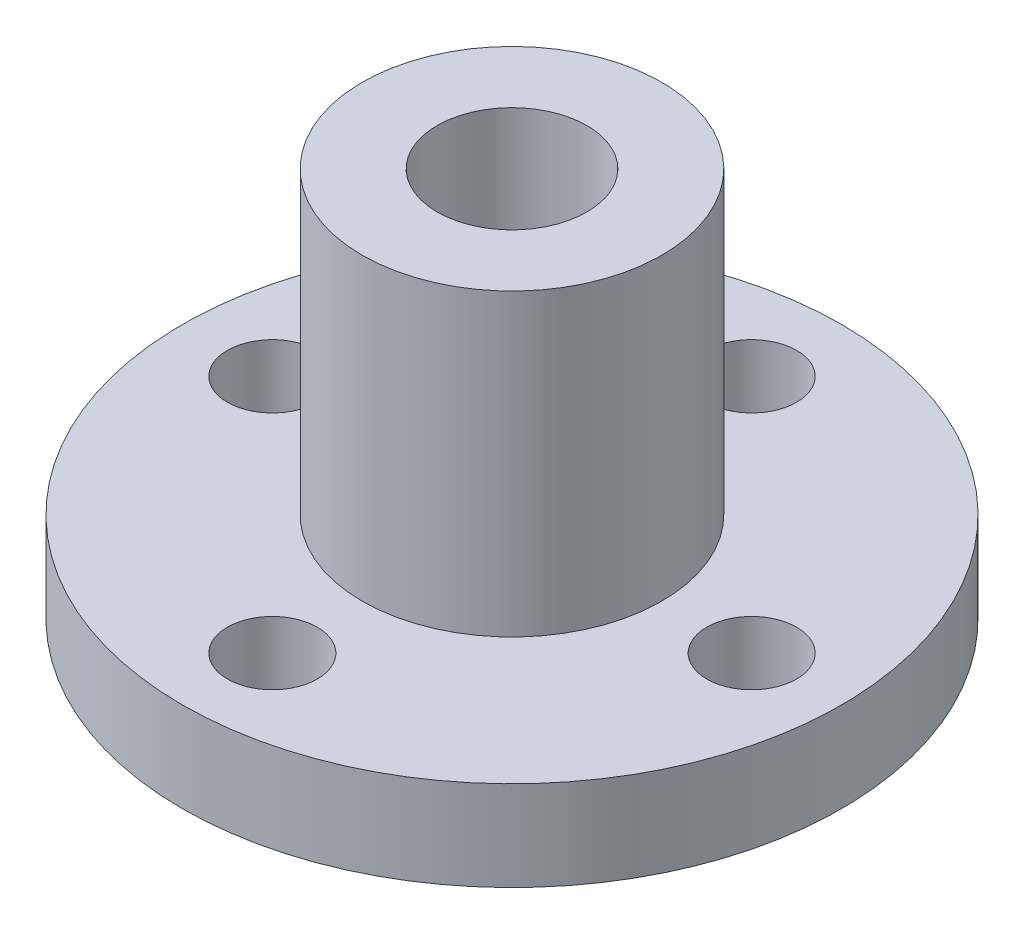
SolidWorks part; units mm, degrees
ref_plane "前视基准面" through (0, 0, 0) normal (0, 0, 1) x (1, 0, 0)
ref_plane "上视基准面" through (0, 0, 0) normal (0, 1, 0) x (1, 0, 0)
ref_plane "右视基准面" through (0, 0, 0) normal (1, 0, 0) x (0, 0, -1)
sketch "草图1" plane through (0, 0, 0) normal (0, 1, 0) x (1, 0, 0)
  circle A0 centre (0, 0) radius 11
  dimension "D1" = 22
extrude "凸台-拉伸1" add sketch "草图1" along normal blind 3
sketch "草图2" plane through (0, 3, 0) normal (0, 1, 0) x (1, 0, 0)
  circle A0 centre (0, 0) radius 5
  dimension "D1" = 10
extrude "凸台-拉伸2" add sketch "草图2" along normal blind 10
sketch "草图3" plane through (0, 13, 0) normal (0, 1, 0) x (1, 0, 0)
  circle A0 centre (0, 0) radius 2.5
  dimension "D1" = 5
extrude "切除-拉伸1" cut sketch "草图3" against normal up to surface (13 mm away) up to face at (0, 0, 11)
sketch "草图4" plane through (0, 0, 0) normal (0, -1, 0) x (1, 0, 0)
  line L0 (0, 0) -> (34.833, 0) construction
  line L1 (0, 0) -> (0, 14.1524) construction
  circle A0 centre (0, 0) radius 8
  circle A1 centre (0, 8) radius 1.5
  circle A2 centre (8, 0) radius 1.5
  circle A3 centre (0, -8) radius 1.5
  circle A4 centre (-8, 0) radius 1.5
  dimension "D1" = 16
  dimension "D2" = 3
extrude "切除-拉伸2" cut sketch "草图4" against normal up to surface (3 mm away) contours A4 | A1 | A2 | A3 up to face at (0, 3, 5)
